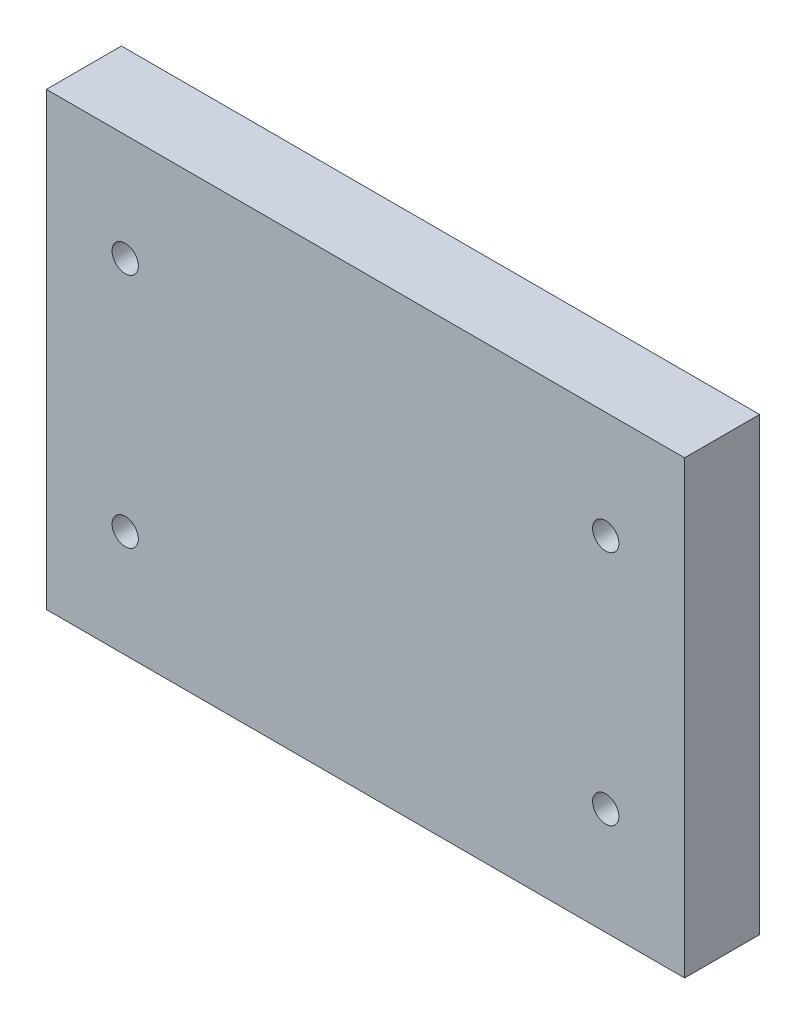
SolidWorks part; units mm, degrees
ref_plane "前视基准面" through (0, 0, 0) normal (0, 0, 1) x (1, 0, 0)
ref_plane "上视基准面" through (0, 0, 0) normal (0, 1, 0) x (1, 0, 0)
ref_plane "右视基准面" through (0, 0, 0) normal (1, 0, 0) x (0, 0, -1)
other "Configuration Table"
sketch "草图1" plane through (0, 0, 0) normal (0, 0, 1) x (1, 0, 0)
  line L1 (-42.5, 30) -> (42.5, 30)
  line L2 (-42.5, 30) -> (-42.5, -30)
  line L3 (-42.5, -30) -> (42.5, -30)
  line L4 (42.5, 30) -> (42.5, -30)
  line L5 (-42.5, 30) -> (42.5, -30) construction
  line L6 (-42.5, -30) -> (42.5, 30) construction
  point P0 (0, 0)
  dimension "D1" = 85
  dimension "D2" = 60
extrude "凸台-拉伸1" add sketch "草图1" along normal blind 10
sketch "草图2" plane through (0, 0, 10) normal (0, 0, 1) x (1, 0, 0)
  line L0 (0, 0) -> (-49.7556, 0) construction
  line L1 (0, 0) -> (0, 26.6228) construction
  circle A0 centre (-32, 15.75) radius 1.75
  circle A1 centre (-32, -15.75) radius 1.75
  circle A2 centre (32, 15.75) radius 1.75
  circle A3 centre (32, -15.75) radius 1.75
  dimension "D1" = 3.5
  dimension "D2" = 31.5
  dimension "D3" = 64
extrude "切除-拉伸1" cut sketch "草图2" against normal blind 10
